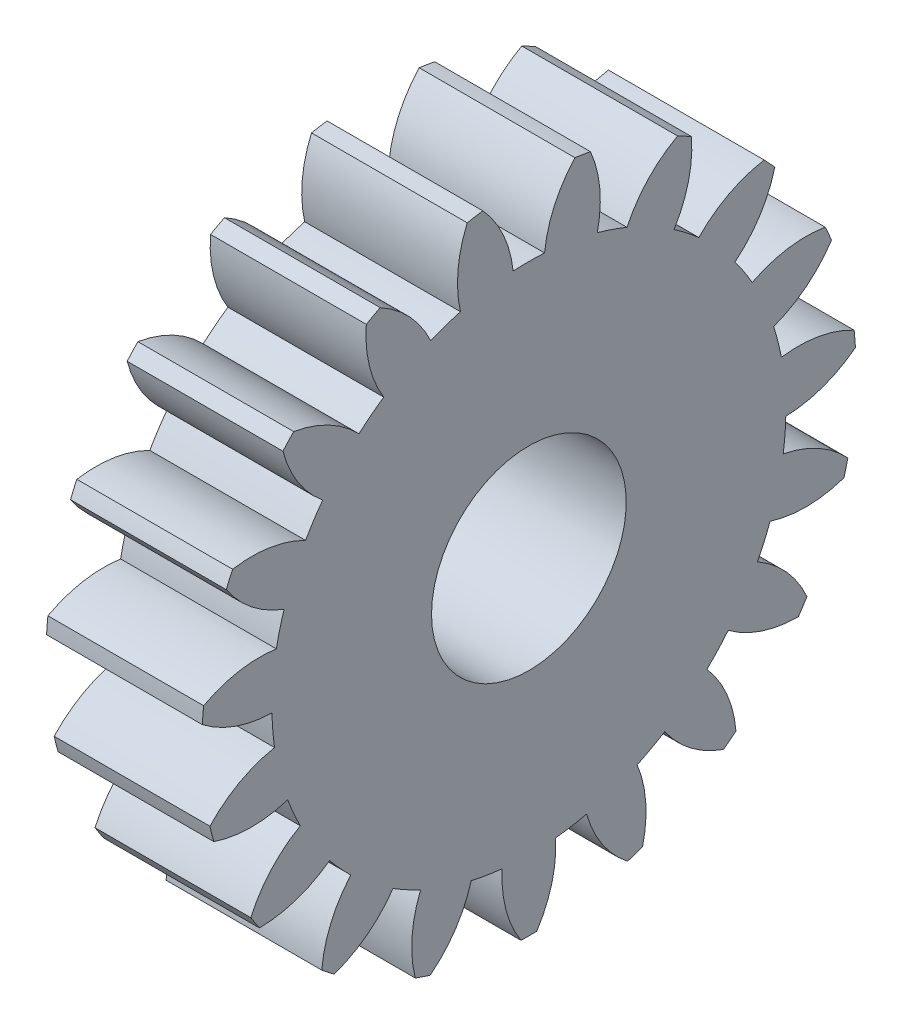
SolidWorks part; units mm, degrees
ref_plane "Plane1" through (0, 0, 0) normal (0, 0, 1) x (1, 0, 0)
ref_plane "Plane2" through (0, 0, 0) normal (0, 1, 0) x (1, 0, 0)
ref_plane "Plane3" through (0, 0, 0) normal (1, 0, 0) x (0, 0, -1)
sketch "HoldingSke" plane through (0, 0, 0) normal (0, 1, 0) x (1, 0, 0)
  line L0 (0, 0) -> (1.1819, -0.407)
  line L1 (-15, 0) -> (100, 0) construction
  line L2 (0, 0) -> (-2.1039, 2.3779)
  line L3 (0, 0) -> (-11.863, 4.5341)
  line L4 (0, 0) -> (8.1655, 2.8116)
  line L5 (0, 0) -> (-46.8476, -17.4728)
  line L6 (0, 0) -> (-3.3159, -2.2372)
  line L7 (-2.1039, 2.3779) -> (8.6586, 51.2059)
  line L8 (-76.2, 54.61) -> (-75.3, 54.61)
  line L9 (-71.009, 38.7566) -> (-53.1078, 45.2721)
  line L10 (-76.2, 71.12) -> (104.1128, 71.12)
  line L11 (0, 0) -> (-4, 0)
  line L12 (-76.2, 101.6) -> (-76.17, 101.6)
  line L13 (24.9733, 27.94) -> (52.9518, 28.4284)
  line L14 (24.9733, 27.94) -> (24.9743, 27.94)
  line L15 (24.9733, 27.94) -> (100.4006, 29.5858)
  line L16 (-63.627, -0.8) -> (-12.827, -0.8)
  circle A0 centre (0, 0) radius 2.5
  circle A1 centre (0, 0) radius 6.599
  circle A2 centre (0, 0) radius 37.5
  circle A3 centre (0, 0) radius 2.5
  dimension "MHD" = 13.198
  dimension "Hub_dia" = 75
  dimension "Bore" = 5
  dimension "MBD" = 5
  dimension "Num_teeth" = 19
  dimension "Pitch" = 1.25
  dimension "Overall_len" = 50
  dimension "Show_teeth" = 19
  dimension "Thickness" = 4
  dimension "OAL" = 50.0001
  dimension "T_dim" = 0.9
  dimension "Ap" = 20
  dimension "H" = 19.05
  dimension "Pitch_radius" = 180.3128
  dimension "Width" = 4
  dimension "Backlash" = 0.03
  dimension "Addendum_fac" = 1
  dimension "Dedendum_fac" = 1.25
  dimension "Clearance_fac" = 0.25
  dimension "Dedendum_add" = 0.001
  dimension "Module" = 0.8
sketch "BasProSke" plane through (0, 0, 0) normal (0, 1, 0) x (1, 0, 0)
  line L0 (-10, 0) -> (60, 0) construction
  line L1 (0, 0) -> (0, 8.4)
  line L2 (0, 0) -> (4, 0)
  line L3 (4, 0) -> (4, 8.4)
  line L4 (4, 8.4) -> (0, 8.4)
  dimension "Thickness" = 4
  dimension "Diameter" = 16.8
revolve "Base-Revolve" add sketch "BasProSke" angle 360 about L0
sketch "TooCutSke" plane through (0, 0, 0) normal (1, 0, 0) x (0, 0, -1)
  line L1 (0, 0) -> (0, 107) construction
  line L2 (0, 0) -> (-0.6801, 7.5695) construction
  line L3 (0, 0) -> (-2.4947, 14.9497) construction
  line L4 (-0.6801, 7.5695) -> (-1.2473, 7.4749) construction
  arc A0 (0.4034, 6.5867) -> (-0.4034, 6.5867) centre (0, 0) ccw
  arc A1 (1.2029, 8.3391) -> (-1.2029, 8.3391) centre (0, 0) ccw
  circle A2 centre (0, 0) radius 7.6 construction
  circle A3 centre (0, 0) radius 7.1417 construction
  arc A4 (-0.4034, 6.5867) -> (-1.2029, 8.3391) centre (-3.4264, 6.266) ccw
  arc A5 (1.2029, 8.3391) -> (0.4034, 6.5867) centre (3.4264, 6.266) ccw
  dimension "Root_dia" = 13.198
  dimension "Overcut_dia" = 16.8508
  dimension "Pitch_dia" = 15.2
  dimension "Base_dia" = 14.2833
  dimension "Flank_rad" = 3.04
  dimension "Half_ang" = 9.474
  dimension "Half_CT" = 0.5751
extrude "ToothCut" cut sketch "TooCutSke" along normal through all
fillet "Breaks" [suppressed] radius 0.016
fillet "RootFillets" [suppressed] radius 0.201
pattern_circular "TeethCuts" count 19 every 18.947 about axis through (-10, 0, 0) along (1, 0, 0) of "ToothCut", "RootFillets", "Breaks"
sketch "HubNeaOneSke" plane through (0, 0, 0) normal (-1, 0, 0) x (0, 0, 1)
  circle A0 centre (0, 0) radius 6.599
  dimension "Diameter" = 13.198
extrude "HubNearOne" [suppressed] add sketch "HubNeaOneSke" along normal blind 46.0001
sketch "HubNeaBotSke" plane through (0, 0, 0) normal (-1, 0, 0) x (0, 0, 1)
  circle A0 centre (0, 0) radius 6.599
  dimension "Diameter" = 13.198
extrude "HubNearBoth" [suppressed] add sketch "HubNeaBotSke" along normal blind 23
ref_plane "FarPln" through (4, 0, 0) normal (1, 0, 0) x (0, 0, -1)
sketch "HubFarSke" plane through (4, 0, 0) normal (1, 0, 0) x (0, 0, -1)
  circle A0 centre (0, 0) radius 6.599
  dimension "Diameter" = 13.198
extrude "HubFar" [suppressed] add sketch "HubFarSke" along normal blind 23
sketch "BorSke" plane through (0, 0, 0) normal (1, 0, 0) x (0, 0, -1)
  circle A0 centre (0, 0) radius 2.5
  dimension "Diameter" = 5
extrude "Bore" cut sketch "BorSke" along normal mid plane 100.0001
sketch "KeySke" plane through (0, 0, 0) normal (1, 0, 0) x (0, 0, -1)
  line L0 (-1, 0) -> (-1, 3.4)
  line L1 (-1, 3.4) -> (1, 3.4)
  line L2 (1, 3.4) -> (1, 0)
  line L3 (0, 0) -> (0, 34) construction
  line L4 (-1, 0) -> (1, 0)
  dimension "Offset" = 3.4
  dimension "Width" = 2
extrude "Keyway" [suppressed] cut sketch "KeySke" along normal mid plane 100.0001
pattern_circular "Keyway2" [suppressed] count 2 every 90 about axis through (-10, 0, 0) along (1, 0, 0)
equation "' \"Module@HoldingSke\" = 6.35"
equation "' \"Num_teeth@HoldingSke\" = 12"
equation "' \"Ap@HoldingSke\" =  20"
equation "' \"Ap@HoldingSke\" = 20"
equation "' \"Width@HoldingSke\" = 0.5 * 25.4"
equation "' \"Hub_dia@HoldingSke\"= 1 * 25.4"
equation "' \"Hub_dia@HoldingSke\" = 1 * 25.4"
equation "' \"Overall_len@HoldingSke\" = 1.0 * 25.4"
equation "' \"Bore@HoldingSke\" = 0.75 * 25.4"
equation "' \"T_dim@HoldingSke\" = 0.1 * 25.4"
equation "' \"Width@KeySke\" = 0.25 * 25.4"
equation "' \"Show_teeth@HoldingSke\" = 13"
equation "' \"Backlash@HoldingSke\" = 0.009 * 25.4"
equation "' \"Addendum_fac@HoldingSke\" = 1.0"
equation "' \"Dedendum_fac@HoldingSke\" = 1.25"
equation "' \"Dedendum_add@HoldingSke\" = 0.00005 * 25.4"
equation "' \"Clearance_fac@HoldingSke\" = 0.25"
equation "\"Pitch@HoldingSke\" = 1 / \"Module@HoldingSke\""
equation "\"Overcut_dia@TooCutSke\" = (\"Num_teeth@HoldingSke\" + 2 * \"Addendum_fac@HoldingSke\") / \"Pitch@HoldingSke\" + 0.002 * 25.4"
equation "\"Pitch_dia@TooCutSke\" = \"Num_teeth@HoldingSke\" / \"Pitch@HoldingSke\""
equation "\"Base_dia@TooCutSke\" = \"Num_teeth@HoldingSke\" / \"Pitch@HoldingSke\" * cos((\"Ap@HoldingSke\"  * 3.14159265 / 180))"
equation "\"Root_dia@TooCutSke\" = (\"Num_teeth@HoldingSke\" + 2) / \"Pitch@HoldingSke\" - 2 * (\"Addendum_fac@HoldingSke\" + \"Dedendum_fac@HoldingSke\") / \"Pitch@HoldingSke\" - \"Dedendum_add@HoldingSke\" * 2"
equation "\"Half_ang@TooCutSke\" = 180 / \"Num_teeth@HoldingSke\""
equation "\"Half_CT@TooCutSke\" = \"Num_teeth@HoldingSke\" / \"Pitch@HoldingSke\" * sin((3.14159265 / 2 / \"Num_teeth@HoldingSke\")) / 2 - 7 * \"Backlash@HoldingSke\" / 4"
equation "\"Flank_rad@TooCutSke\" = \"Num_teeth@HoldingSke\" / \"Pitch@HoldingSke\" / 5"
equation "\"Radius@RootFillets\" = \"Clearance_fac@HoldingSke\" / \"Pitch@HoldingSke\" + \"Dedendum_add@HoldingSke\""
equation "\"Break_rad@Breaks\" = 0.02 / \"Pitch@HoldingSke\""
equation "\"Thickness@HoldingSke\" = \"Width@HoldingSke\""
equation "\"OAL@HoldingSke\" = \"Thickness@HoldingSke\""
equation "\"MHD@HoldingSke\" = (\"Num_teeth@HoldingSke\" + 2) / \"Pitch@HoldingSke\" - 2 * (\"Addendum_fac@HoldingSke\" + \"Dedendum_fac@HoldingSke\")  / \"Pitch@HoldingSke\" - \"Dedendum_add@HoldingSke\" * 2"
equation "\"MBD@HoldingSke\" = (\"Num_teeth@HoldingSke\" + 2) / \"Pitch@HoldingSke\" - 2 * (\"Addendum_fac@HoldingSke\" + \"Dedendum_fac@HoldingSke\")  / \"Pitch@HoldingSke\" - \"Dedendum_add@HoldingSke\" * 2 - 0.002 * 25.4"
equation "\"MHD@HoldingSke\" = ((sgn( \"MHD@HoldingSke\" - \"Hub_dia@HoldingSke\" )-1)*( \"MHD@HoldingSke\" - \"Hub_dia@HoldingSke\" ))/-2+ \"Hub_dia@HoldingSke\""
equation "\"MBD@HoldingSke\" = ((sgn( \"MBD@HoldingSke\" - \"Bore@HoldingSke\" )-1)*( \"MBD@HoldingSke\" - \"Bore@HoldingSke\" ))/-2+ \"Bore@HoldingSke\""
equation "\"OAL@HoldingSke\" = ((sgn( \"OAL@HoldingSke\" - \"Overall_len@HoldingSke\" )+1)*( \"OAL@HoldingSke\" - \"Overall_len@HoldingSke\" ))/2 + \"Overall_len@HoldingSke\" + 0.000002 * 25.4"
equation "\"Num_teeth@TeethCuts\" = int( \"Show_teeth@HoldingSke\" ) + 1"
equation "\"Num_teeth@TeethCuts\" = ((sgn( \"Num_teeth@TeethCuts\" - \"Num_teeth@HoldingSke\" )-1)*( \"Num_teeth@TeethCuts\" - \"Num_teeth@HoldingSke\" ))/-2+ \"Num_teeth@HoldingSke\""
equation "\"Num_teeth@TeethCuts\" = ((sgn( \"Num_teeth@TeethCuts\" - 2.0)+1)*( \"Num_teeth@TeethCuts\" - 2.0))/2 +2.0"
equation "\"Angle@TeethCuts\" = 360.0 / \"Num_teeth@HoldingSke\""
equation "\"Diameter@BasProSke\" = (\"Num_teeth@HoldingSke\" + 2 * \"Addendum_fac@HoldingSke\") / \"Pitch@HoldingSke\""
equation "\"Thickness@BasProSke\"  = \"Thickness@HoldingSke\""
equation "' \"Fillet_rad@BasProSke\" =  \"Thickness@HoldingSke\" * 0.05"
equation "' \"Fillet_rad@BasProSke\" = \"Thickness@HoldingSke\" * 0.05"
equation "\"MHD@HoldingSke\" = ((sgn( \"MHD@HoldingSke\" - \"Root_dia@TooCutSke\" )-1)*( \"MHD@HoldingSke\" - \"Root_dia@TooCutSke\" ))/-2+ \"Root_dia@TooCutSke\""
equation "\"Diameter@HubNeaOneSke\" = \"MHD@HoldingSke\""
equation "\"Length@HubNearOne\" = \"OAL@HoldingSke\" - \"Thickness@BasProSke\""
equation "\"Diameter@HubNeaBotSke\" = \"MHD@HoldingSke\""
equation "\"Length@HubNearBoth\" = ( \"OAL@HoldingSke\" - \"Thickness@BasProSke\" ) / 2.0"
equation "\"Thickness@FarPln\" = \"Thickness@BasProSke\""
equation "\"Diameter@HubFarSke\" = \"MHD@HoldingSke\""
equation "\"Length@HubFar\" = ( \"OAL@HoldingSke\" - \"Thickness@BasProSke\" ) / 2.0"
equation "\"Diameter@BorSke\" = \"MBD@HoldingSke\""
equation "\"D1@Bore\" = \"OAL@HoldingSke\" * 2.0"
equation "\"D1@Keyway\" = \"OAL@HoldingSke\" * 2.0"
equation "\"Offset@KeySke\" = \"T_dim@HoldingSke\" + \"MBD@HoldingSke\" / 2.0"
